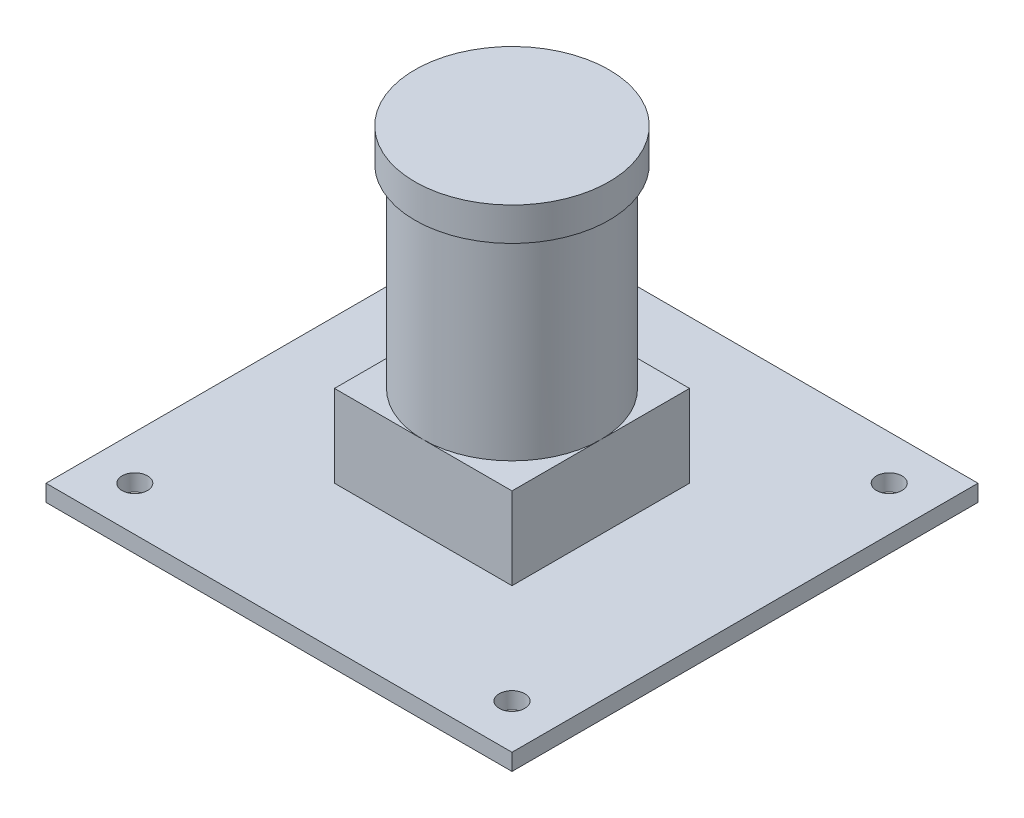
SolidWorks part; units mm, degrees
ref_plane "前视基准面" through (0, 0, 0) normal (0, 0, 1) x (1, 0, 0)
ref_plane "上视基准面" through (0, 0, 0) normal (0, 1, 0) x (1, 0, 0)
ref_plane "右视基准面" through (0, 0, 0) normal (1, 0, 0) x (0, 0, -1)
sketch "草图1" plane through (0, 0, 0) normal (0, 1, 0) x (1, 0, 0)
  line L1 (-21, 21) -> (21, 21)
  line L2 (-21, 21) -> (-21, -21)
  line L3 (-21, -21) -> (21, -21)
  line L4 (21, 21) -> (21, -21)
  line L5 (-21, 21) -> (21, -21) construction
  line L6 (-21, -21) -> (21, 21) construction
  point P0 (0, 0)
  dimension "D1" = 42
extrude "凸台-拉伸1" add sketch "草图1" along normal blind 1.5
sketch "草图2" plane through (0, 1.5, 0) normal (0, 1, 0) x (1, 0, 0)
  line L0 (-17, 0) -> (17, 0) construction
  line L1 (-17, 17) -> (17, 17) construction
  line L2 (-17, 17) -> (-17, -17) construction
  line L3 (-17, -17) -> (17, -17) construction
  line L4 (17, 17) -> (17, -17) construction
  line L5 (-17, 17) -> (17, -17) construction
  line L6 (-17, -17) -> (17, 17) construction
  circle A0 centre (-17, 17) radius 1.15
  circle A1 centre (17, 17) radius 1.15
  circle A2 centre (-17, -17) radius 1.15
  circle A3 centre (17, -17) radius 1.15
  point P0 (0, 0)
  dimension "D3" = 2.3
  dimension "D4" = 2.3
  dimension "D1" = 34
  dimension "D2" = 34
extrude "切除-拉伸1" cut sketch "草图2" against normal blind 2
sketch "草图3" plane through (0, 1.5, 0) normal (0, 1, 0) x (1, 0, 0)
  circle A0 centre (0, 0) radius 8
  dimension "D1" = 16
extrude "凸台-拉伸2" add sketch "草图3" along normal blind 24.9
sketch "草图4" plane through (0, 1.5, 0) normal (0, 1, 0) x (1, 0, 0)
  line L1 (-8, 8) -> (8, 8)
  line L2 (-8, 8) -> (-8, -8)
  line L3 (-8, -8) -> (8, -8)
  line L4 (8, 8) -> (8, -8)
  line L5 (-8, 8) -> (8, -8) construction
  line L6 (-8, -8) -> (8, 8) construction
  point P0 (0, 0)
  dimension "D1" = 16
extrude "凸台-拉伸3" add sketch "草图4" along normal blind 7.4
sketch "草图5" plane through (0, 26.4, 0) normal (0, 1, 0) x (1, 0, 0)
  circle A0 centre (0, 0) radius 8.75
  dimension "D1" = 17.5
extrude "凸台-拉伸4" add sketch "草图5" along normal blind 3
